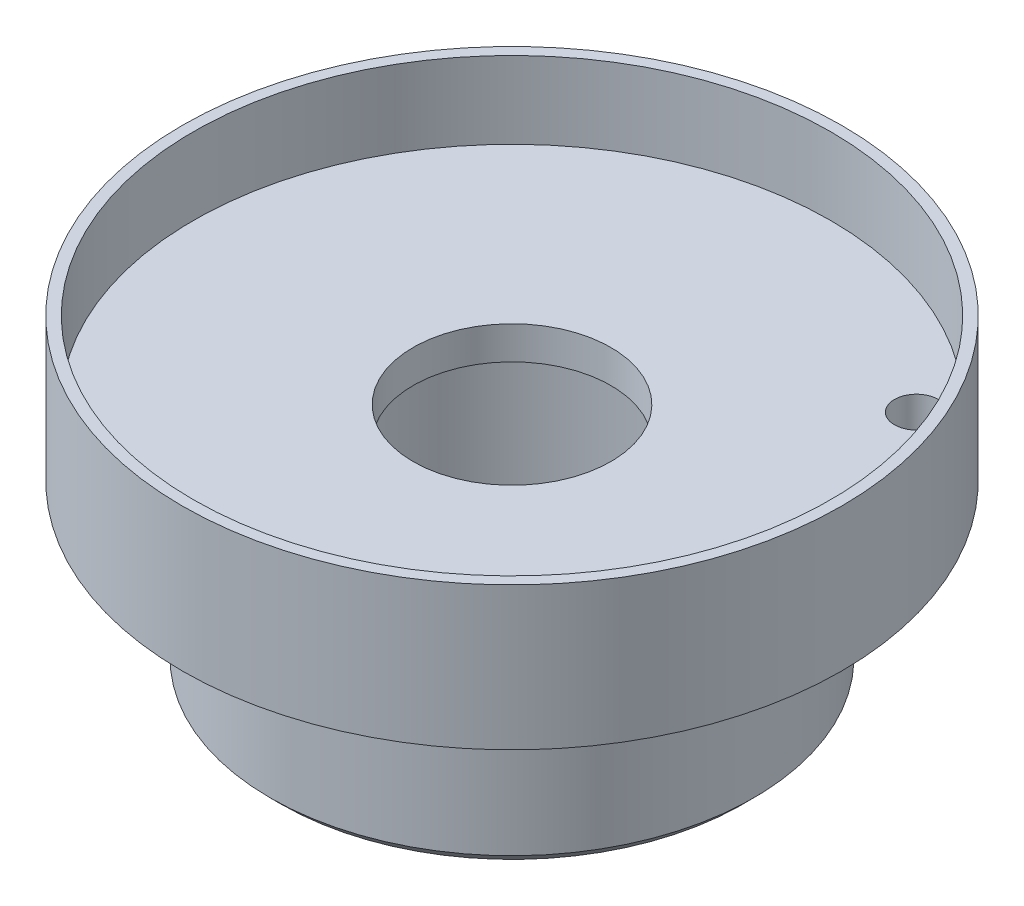
SolidWorks part; units mm, degrees
material "Alliage de zinc AC41A, brut"
ref_plane "Plan de face" through (0, 0, 0) normal (0, 0, 1) x (1, 0, 0)
ref_plane "Plan de dessus" through (0, 0, 0) normal (0, 1, 0) x (1, 0, 0)
ref_plane "Plan de droite" through (0, 0, 0) normal (1, 0, 0) x (0, 0, -1)
sketch "Esquisse1" plane through (0, 0, 0) normal (0, 1, 0) x (1, 0, 0)
  circle A0 centre (0, 0) radius 11
  dimension "D1" = 22
extrude "Boss.-Extru.1" add sketch "Esquisse1" along normal blind 7.5
sketch "Esquisse3" plane through (0, 7.5, 0) normal (0, 1, 0) x (1, 0, 0)
  circle A0 centre (0, 0) radius 15
  dimension "D1" = 30
extrude "Boss.-Extru.2" add sketch "Esquisse3" along normal blind 6.5
chamfer "Chanfrein1" distance 0.5 angle 45 1 edges at (0, 0, 11)
chamfer "Chanfrein2" distance 1 angle 45 1 edges at (0, 7.5, 11)
sketch "Esquisse4" plane through (0, 14, 0) normal (0, 1, 0) x (1, 0, 0)
  circle A0 centre (0, 0) radius 14.5
  dimension "D1" = 29
extrude "Enlèv. mat.-Extru.1" cut sketch "Esquisse4" against normal blind 3.5
sketch "Esquisse5" plane through (0, 10.5, 0) normal (0, 1, 0) x (1, 0, 0)
  circle A0 centre (0, 0) radius 4.5
  dimension "D1" = 9
extrude "Enlèv. mat.-Extru.2" cut sketch "Esquisse5" against normal blind 1.5 contours A0
sketch "Esquisse6" plane through (0, 9, 0) normal (0, 1, 0) x (1, 0, 0)
  circle A0 centre (0, 0) radius 7
  dimension "D1" = 14
extrude "Enlèv. mat.-Extru.3" cut sketch "Esquisse6" against normal blind 1
sketch "Esquisse20" plane through (0, 8, 0) normal (0, 1, 0) x (1, 0, 0)
  circle A0 centre (0, 0) radius 8
  dimension "D1" = 16
extrude "Enlèv. mat.-Extru.4" cut sketch "Esquisse20" against normal blind 8
cosmetic thread "Représentation de filetage1" parameters "D1"=4, "D2"=17
sketch "Sketch4" plane through (0, 7.5, 0) normal (0, -1, 0) x (-1, 0, 0)
  line L1 (0, 0) -> (-9.5, 0) construction
  line L2 (0, 0) -> (0, 8.9) construction
  line L3 (0, 8.9) -> (-9.5, 8.9) construction
  line L4 (-9.5, 0) -> (-9.5, 8.9) construction
  point P2 (-9.5, 8.9)
  point P40 (-9.5, 8.9)
  dimension "D1" = 8.9
  dimension "D2" = 9.5
hole_wizard "Ø2.0 (2) Diameter Hole1" positions "Sketch4" profile "Sketch3" hole size "Ø2.0" standard "ISO" end condition up to next
sketch "Sketch3" plane through (9.5, 7.5, -8.9) normal (1, 0, 0) x (0, 0, -1)
  line L0 (0, 0) -> (0, 3)
  line L1 (0, 3) -> (1, 3)
  line L2 (1, 3) -> (1, 0)
  line L5 (1, 0) -> (0, 0)
  line L11 (0, -6.35) -> (0, 107.95) construction
  dimension "Thru Hole Dia." = 2
  dimension "Thru Hole Depth" = 3
